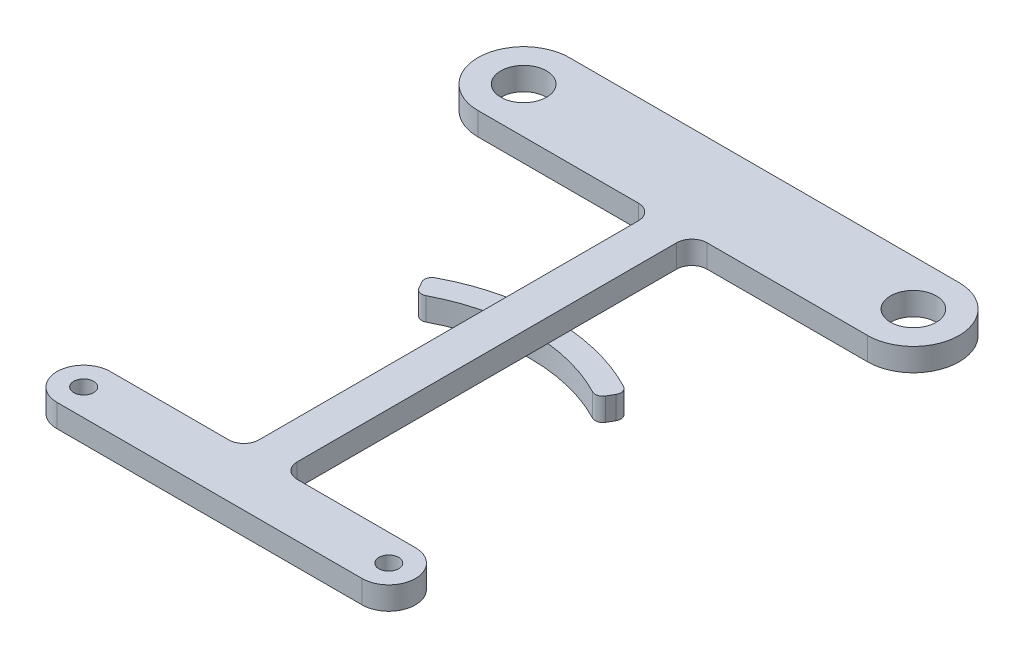
SolidWorks part; units mm, degrees
ref_plane "Front Plane" through (0, 0, 0) normal (0, 0, 1) x (1, 0, 0)
ref_plane "Top Plane" through (0, 0, 0) normal (0, 1, 0) x (1, 0, 0)
ref_plane "Right Plane" through (0, 0, 0) normal (1, 0, 0) x (0, 0, -1)
sketch "Sketch1" plane through (0, 0, 0) normal (0, 1, 0) x (1, 0, 0)
  line L0 (0, 0) -> (0, 48.24) construction
  line L5 (-25.55, 48.24) -> (25.55, 48.24) construction
  line L6 (-25.55, 48.24) -> (25.55, 48.24) construction
  line L7 (-25.55, 54.24) -> (25.55, 54.24)
  line L8 (-25.55, 42.24) -> (-2.5, 42.24)
  line L9 (-20, -15) -> (20, -15) construction
  line L10 (-20, -11.5) -> (-2.5, -11.5)
  line L11 (-20, -18.5) -> (20, -18.5)
  line L12 (-2.5, 42.24) -> (-2.5, -11.5)
  line L13 (2.5, 42.24) -> (2.5, -11.5)
  line L14 (2.5, -11.5) -> (20, -11.5)
  line L15 (2.5, 42.24) -> (25.55, 42.24)
  line L16 (0, -15) -> (0, 0) construction
  circle A0 centre (-20, -15) radius 1.3
  circle A1 centre (20, -15) radius 1.3
  circle A8 centre (25.55, 48.24) radius 3
  circle A9 centre (-25.55, 48.24) radius 3
  arc A10 (-25.55, 54.24) -> (-25.55, 42.24) centre (-25.55, 48.24) ccw
  arc A11 (25.55, 42.24) -> (25.55, 54.24) centre (25.55, 48.24) ccw
  arc A12 (-20, -11.5) -> (-20, -18.5) centre (-20, -15) ccw
  arc A13 (20, -18.5) -> (20, -11.5) centre (20, -15) ccw
  point P0 (0, 4)
  point P10 (0, -15)
  point P20 (0, 0)
  point P21 (0, 0)
  point P22 (0, 0)
  point P23 (0, 48.24)
  point P24 (0, 0)
  point P25 (0, 0)
  point P26 (0, 0)
  point P28 (0, 48.24)
  point P34 (0, 0)
  point P35 (0, 0)
  point P36 (-25.55, 42.24)
  point P37 (-25.55, 42.24)
  point P38 (0, 0)
  point P39 (0, 0)
  point P40 (25.55, 54.24)
  point P41 (-29.3015, 52.9225)
  point P42 (-25.55, 42.24)
  point P43 (-30.0221, 52.24)
  point P44 (-25.55, 42.24)
  point P45 (-25.55, 42.24)
  point P46 (0, 0)
  point P47 (0, 0)
  point P48 (2.5, 42.24)
  point P49 (-30.0221, 52.24)
  point P50 (-30.0221, 52.24)
  point P51 (-2.5, 42.24)
  point P52 (-25.55, 42.24)
  point P53 (0, 0)
  point P54 (25.55, 42.24)
  dimension "D5" = 2.6
  dimension "D17" = 6
  dimension "D2" = 7
  dimension "D3" = 40
  dimension "D4" = 5
  dimension "D6" = 15
  dimension "D7" = 53.74
  dimension "D14" = 4
  dimension "D15" = 51.1
  dimension "D16" = 48.24
  dimension "40" = 40
extrude "Boss-Extrude4" add sketch "Sketch1" along normal blind 3
sketch "Sketch2" plane through (0, 0, 0) normal (0, 1, 0) x (1, 0, 0)
  line L0 (0, 0) -> (-13.25, 22.9497) construction
  line L1 (0, 0) -> (13.25, 22.9497) construction
  line L2 (0, 0) -> (0, 26.5) construction
  line L3 (-11.75, 20.3516) -> (-13.25, 22.9497)
  line L4 (13.25, 22.9497) -> (11.75, 20.3516)
  arc A0 (13.25, 22.9497) -> (-13.25, 22.9497) centre (0, 0) ccw
  arc A1 (11.75, 20.3516) -> (-11.75, 20.3516) centre (0, 0) ccw
  dimension "D1" = 53
  dimension "D4" = 47
  dimension "D2" = 60
  dimension "D3" = 30
extrude "Boss-Extrude5" add sketch "Sketch2" against normal blind 3
fillet "Fillet4" radius 1 4 edges at (-11.75, -1.5, -20.3516) (-13.25, -1.5, -22.9497) (11.75, -1.5, -20.3516) (13.25, -1.5, -22.9497)
fillet "Fillet5" radius 2 4 edges at (-2.5, 1.5, -42.24) (2.5, 1.5, -42.24) (2.5, 1.5, 11.5) (-2.5, 1.5, 11.5)
